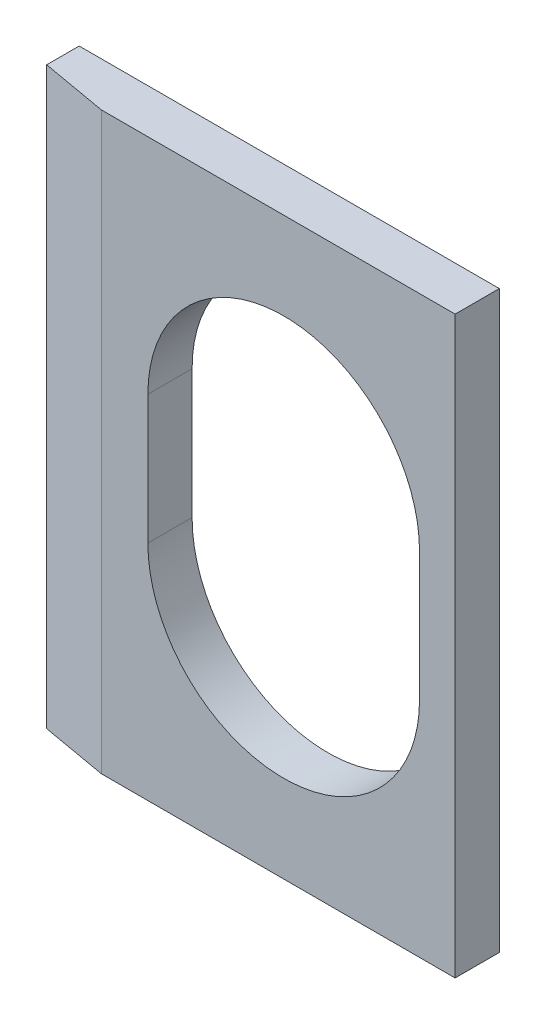
SolidWorks part; units mm, degrees
material "MDF"
ref_plane "Front Plane" through (0, 0, 0) normal (0, 0, 1) x (1, 0, 0)
ref_plane "Top Plane" through (0, 0, 0) normal (0, 1, 0) x (1, 0, 0)
ref_plane "Right Plane" through (0, 0, 0) normal (1, 0, 0) x (0, 0, -1)
sketch "Sketch1" plane through (0, 0, 0) normal (0, 0, 1) x (1, 0, 0)
  line L1 (-60.325, -82.55) -> (60.325, -82.55)
  line L2 (-60.325, -82.55) -> (-60.325, 82.55)
  line L3 (-60.325, 82.55) -> (60.325, 82.55)
  line L4 (60.325, -82.55) -> (60.325, 82.55)
  line L5 (-60.325, -82.55) -> (60.325, 82.55) construction
  line L6 (-60.325, 82.55) -> (60.325, -82.55) construction
  point P0 (0, 0)
  dimension "D1" = 165.1
  dimension "D2" = 120.65
extrude "Boss-Extrude1" add sketch "Sketch1" along normal blind 12.7
sketch "Sketch2" plane through (0, 0, 12.7) normal (0, 0, 1) x (1, 0, 0)
  line L0 (11.0998, 18.5039) -> (11.0998, -18.5039) construction
  line L1 (60.325, -82.55) -> (60.325, 82.55) construction
  line L2 (50.1015, 18.5039) -> (50.1015, -18.5039)
  line L3 (-27.9019, 18.5039) -> (-27.9019, -18.5039)
  line L5 (55, 0) -> (-55, 0) construction
  arc A0 (50.1015, 18.5039) -> (-27.9019, 18.5039) centre (11.0998, 18.5039) ccw
  arc A1 (-27.9019, -18.5039) -> (50.1015, -18.5039) centre (11.0998, -18.5039) ccw
  point P5 (11.0998, 0)
  dimension "D2" = 115.0112
  dimension "D1" = 78.0034
  dimension "D3" = 49.2252
extrude "Cut-Extrude1" cut sketch "Sketch2" against normal up to next
sketch "Sketch3" plane through (0, 82.55, 0) normal (0, 1, 0) x (1, 0, 0)
  line L0 (-41.2762, -12.7) -> (-60.325, -9.3412)
  line L4 (-60.325, -9.3412) -> (-60.325, -12.7)
  line L5 (-60.325, -12.7) -> (-41.2762, -12.7)
  dimension "D1" = 10
  dimension "D2" = 19.0488
extrude "Cut-Extrude2" cut sketch "Sketch3" against normal up to next
